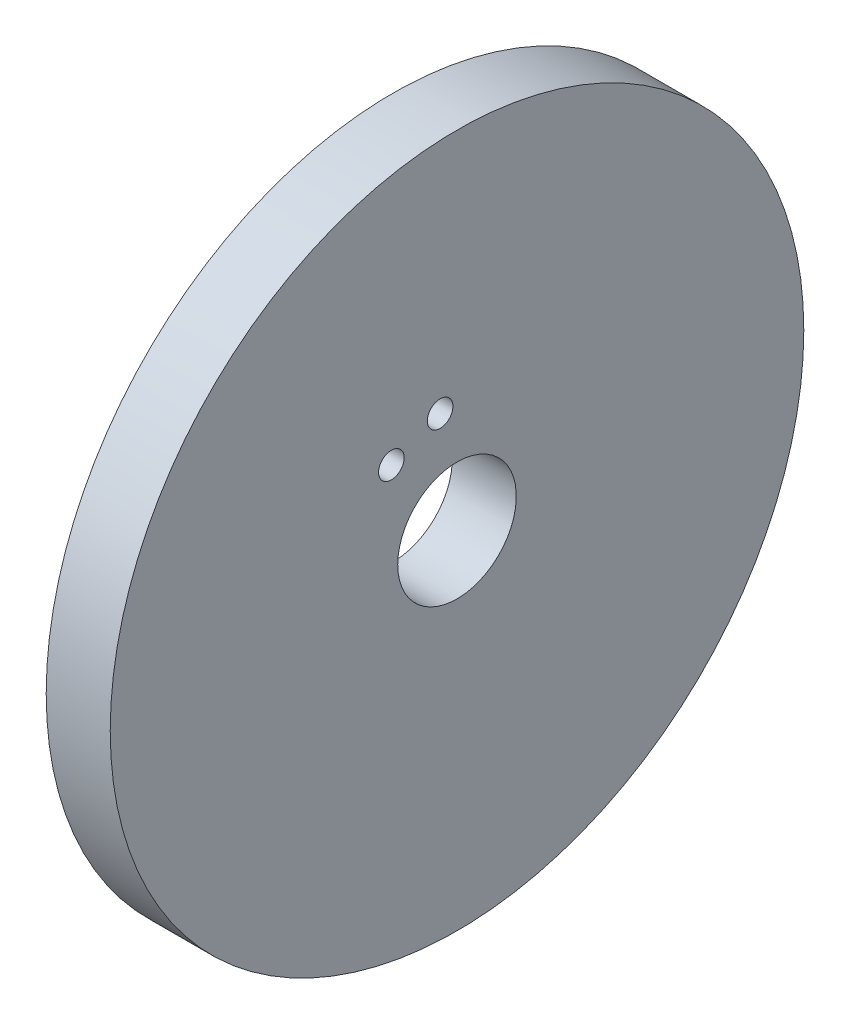
SolidWorks part; units mm, degrees
material "AISI 304"
ref_plane "Front Plane" through (0, 0, 0) normal (0, 0, 1) x (1, 0, 0)
ref_plane "Top Plane" through (0, 0, 0) normal (0, 1, 0) x (1, 0, 0)
ref_plane "Right Plane" through (0, 0, 0) normal (1, 0, 0) x (0, 0, -1)
sketch "Axial profile (mm)" plane through (0, 0, 0) normal (0, 0, 1) x (1, 0, 0)
  line L0 (-110, 0) -> (75, 0) construction
  line L1 (13.7, 11.1125) -> (25.7, 11.1125)
  line L2 (25.7, 11.1125) -> (25.7, 65)
  line L3 (25.7, 65) -> (13.7, 65)
  line L4 (13.7, 65) -> (13.7, 11.1125)
revolve "Full revolution" add sketch "Axial profile (mm)" angle 360 about L0
sketch "Sketch2" plane through (0, 0, 0) normal (1, 0, 0) x (0, 0, -1)
  circle A0 centre (-3.1638, 20.558) radius 2.4
  circle A1 centre (-12.2995, 16.7738) radius 2.4
extrude "Axial holes" cut sketch "Sketch2" along normal through all and the other way through all
sketch "Sketch3" plane through (0, 0, 0) normal (1, 0, 0) x (0, 0, -1)
  circle A0 centre (-31.8198, 31.8198) radius 1.55
  circle A1 centre (-31.8198, -31.8198) radius 1.55
  circle A2 centre (31.8198, -31.8198) radius 1.55
  circle A3 centre (31.8198, 31.8198) radius 1.55
extrude "Cut-Extrude2" cut sketch "Sketch3" along normal blind 7 from offset 13.7
